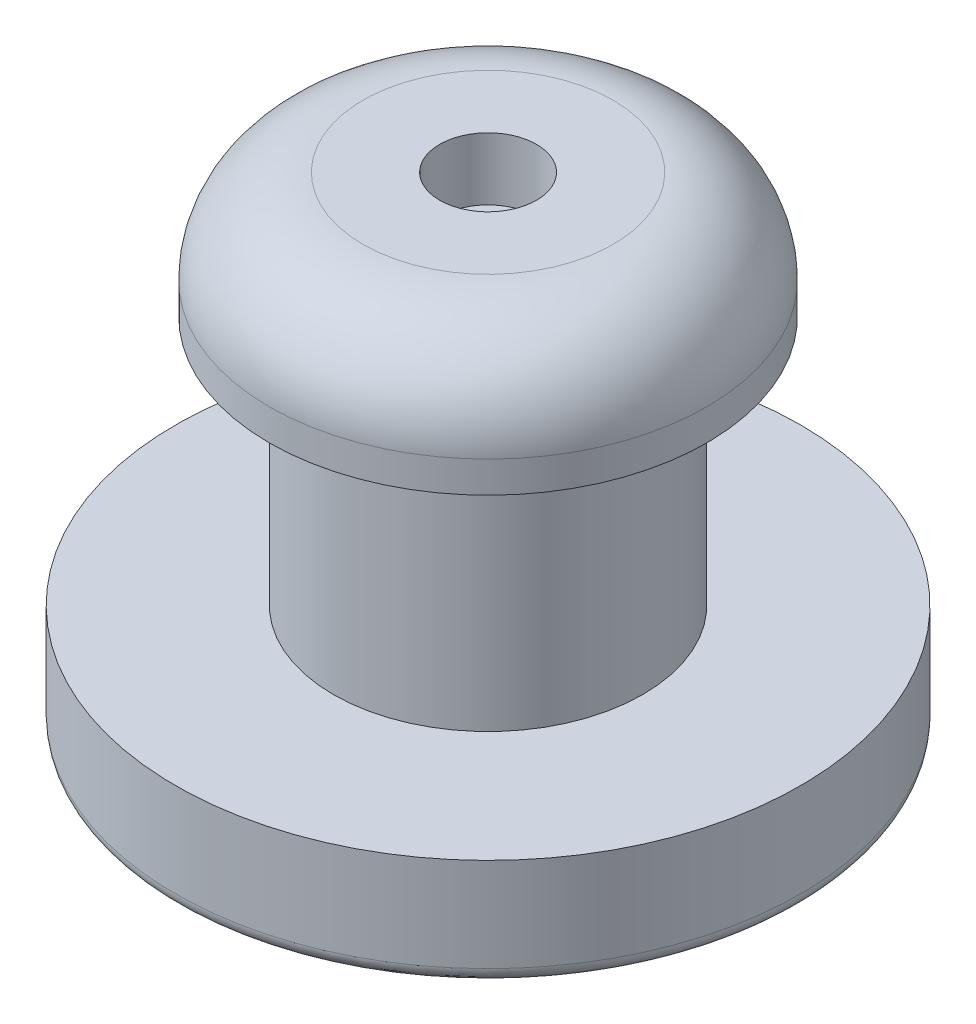
SolidWorks part; units mm, degrees
ref_plane "Front Plane" through (0, 0, 0) normal (0, 0, 1) x (1, 0, 0)
ref_plane "Top Plane" through (0, 0, 0) normal (0, 1, 0) x (1, 0, 0)
ref_plane "Right Plane" through (0, 0, 0) normal (1, 0, 0) x (0, 0, -1)
sketch "Sketch1" plane through (0, 0, 0) normal (0, 1, 0) x (1, 0, 0)
  circle A0 centre (0, 0) radius 4.95
  dimension "D1" = 9.9
extrude "Boss-Extrude1" add sketch "Sketch1" along normal blind 9
sketch "Sketch2" plane through (0, 0, 0) normal (0, -1, 0) x (1, 0, 0)
  circle A0 centre (0, 0) radius 10
  dimension "D1" = 20
extrude "Boss-Extrude2" add sketch "Sketch2" along normal blind 3.5
sketch "Sketch3" plane through (0, -3.5, 0) normal (0, -1, 0) x (1, 0, 0)
  circle A0 centre (0, 0) radius 9
  dimension "D1" = 18
extrude "Cut-Extrude1" cut sketch "Sketch3" against normal blind 1.5
sketch "Sketch4" plane through (0, 9, 0) normal (0, 1, 0) x (1, 0, 0)
  circle A0 centre (0, 0) radius 1.55
  dimension "D1" = 3.1
extrude "Cut-Extrude2" cut sketch "Sketch4" against normal through all
sketch "Sketch5" plane through (0, -2, 0) normal (0, -1, 0) x (1, 0, 0)
  line L1 (1.7032, 2.95) -> (-1.7032, 2.95)
  line L2 (-1.7032, 2.95) -> (-3.4064, 0)
  line L3 (-3.4064, 0) -> (-1.7032, -2.95)
  line L4 (-1.7032, -2.95) -> (1.7032, -2.95)
  line L5 (1.7032, -2.95) -> (3.4064, 0)
  line L6 (3.4064, 0) -> (1.7032, 2.95)
  circle A0 centre (0, 0) radius 2.95 construction
  dimension "D1" = 5.9
extrude "Cut-Extrude3" cut sketch "Sketch5" against normal blind 2.5
fillet "Fillet1" radius 0.5 1 edges at (0, -3.5, -10)
ref_plane "Plane1" through (0, 8, 0) normal (0, 1, 0) x (1, 0, 0)
sketch "Sketch6" plane through (0, 8, 0) normal (0, 1, 0) x (1, 0, 0)
  circle A0 centre (0, 0) radius 5.05
  circle A1 centre (0, 0) radius 7
  dimension "D1" = 10.1
  dimension "D2" = 14
extrude "Boss-Extrude3" add sketch "Sketch6" along normal blind 2 separate body
sketch "Sketch7" plane through (0, 10, 0) normal (0, 1, 0) x (1, 0, 0)
  circle A1 centre (0, 0) radius 7
  circle A2 centre (0, 0) radius 7
  dimension "D1" = 0
extrude "Boss-Extrude4" add sketch "Sketch7" along normal blind 2
sketch "Sketch8" plane through (0, 12, 0) normal (0, 1, 0) x (1, 0, 0)
  circle A0 centre (0, 0) radius 1.55 construction
  circle A1 centre (0, 0) radius 1.55
extrude "Cut-Extrude4" cut sketch "Sketch8" against normal through all
fillet "Fillet2" radius 3 1 edges at (0, 12, 7)
